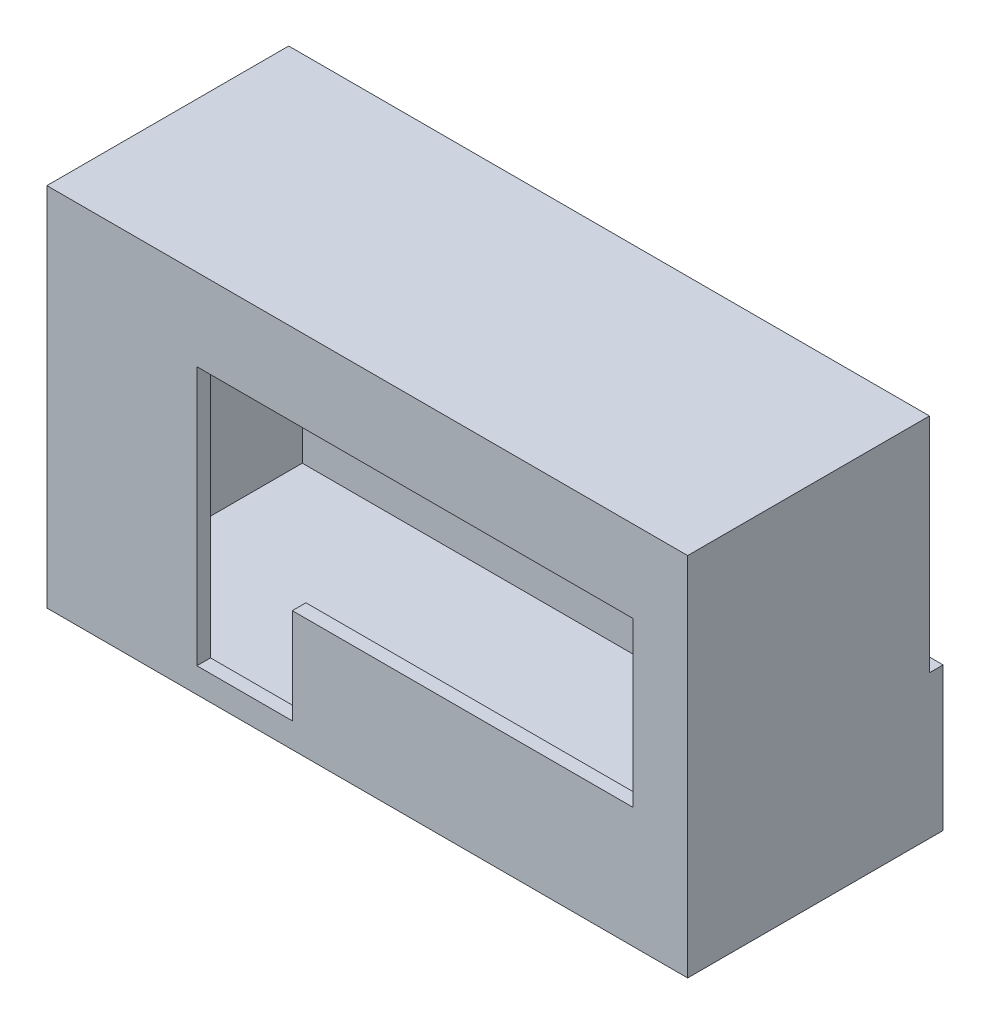
SolidWorks part; units mm, degrees
ref_plane "Спереди" through (0, 0, 0) normal (0, 0, 1) x (1, 0, 0)
ref_plane "Сверху" through (0, 0, 0) normal (0, 1, 0) x (1, 0, 0)
ref_plane "Справа" through (0, 0, 0) normal (1, 0, 0) x (0, 0, -1)
sketch "Эскиз16" plane through (0, 0, 0) normal (0, 0, 1) x (1, 0, 0)
  line L1 (0, 0) -> (-4500, 0)
  line L2 (0, 0) -> (0, 2500)
  line L3 (0, 2500) -> (-4500, 2500)
  line L4 (-4500, 0) -> (-4500, 2500)
  line L5 (-3500, 100) -> (-2800, 100)
  line L6 (-3500, 100) -> (-3500, 2000)
  line L7 (-3500, 2000) -> (-2800, 2000)
  line L8 (-2800, 100) -> (-2800, 2000)
  line L9 (-2800, 2000) -> (-300, 2000)
  line L10 (-2800, 2000) -> (-2800, 800)
  line L11 (-2800, 800) -> (-300, 800)
  line L12 (-300, 2000) -> (-300, 800)
  dimension "D1" = 2500
  dimension "D2" = 4500
  dimension "D3" = 800
  dimension "D4" = 100
  dimension "D5" = 1200
  dimension "D6" = 700
  dimension "D7" = 1000
  dimension "D8" = 300
extrude "Бобышка-Вытянуть5" add sketch "Эскиз16" along normal blind 100 contours L4 L1 L2 L3 L9 L12 L11 L8 L5 L6 L7
sketch "Эскиз19" plane through (0, 0, 0) normal (1, 0, 0) x (0, 0, -1)
  line L1 (-100, 0) -> (1673.5044, 0)
  line L2 (-100, 0) -> (-100, -83.5019)
  line L3 (-100, -83.5019) -> (1673.5044, -83.5019)
  line L4 (1673.5044, 0) -> (1673.5044, -83.5019)
  line L5 (1673.5044, 0) -> (-100, 0)
  line L6 (1673.5044, 0) -> (1673.5044, 2500)
  line L7 (1673.5044, 2500) -> (-100, 2500)
  line L8 (-100, 0) -> (-100, 2500)
extrude "Бобышка-Вытянуть6" add sketch "Эскиз19" against normal blind 4500 contours L4 L1 L2 L3
sketch "Эскиз20" plane through (0, 0, 0) normal (1, 0, 0) x (0, 0, -1)
  line L0 (1673.5044, 0) -> (1673.5044, -83.5019) construction
  line L1 (-100, 2500) -> (1673.5044, 2500)
  line L2 (-100, 2500) -> (-100, -83.5019)
  line L3 (-100, -83.5019) -> (1673.5044, -83.5019)
  line L4 (1673.5044, 2500) -> (1673.5044, -83.5019)
extrude "Бобышка-Вытянуть7" add sketch "Эскиз20" along normal blind 100
sketch "Эскиз21" plane through (-4500, 0, 0) normal (-1, 0, 0) x (0, 0, 1)
  line L1 (100, 2500) -> (-1673.5044, 2500)
  line L2 (100, 2500) -> (100, -83.5019)
  line L3 (100, -83.5019) -> (-1673.5044, -83.5019)
  line L4 (-1673.5044, 2500) -> (-1673.5044, -83.5019)
extrude "Бобышка-Вытянуть8" add sketch "Эскиз21" along normal blind 100 contours L2 L1 L4 L3
sketch "Эскиз22" plane through (0, 2500, 0) normal (0, 1, 0) x (1, 0, 0)
  line L1 (-4600, 1673.5044) -> (100, 1673.5044)
  line L2 (-4600, 1673.5044) -> (-4600, -100)
  line L3 (-4600, -100) -> (100, -100)
  line L4 (100, 1673.5044) -> (100, -100)
extrude "Бобышка-Вытянуть9" add sketch "Эскиз22" along normal blind 100
sketch "Эскиз23" plane through (0, 0, -1673.5044) normal (0, 0, -1) x (-1, 0, 0)
  line L0 (4600, 2600) -> (4600, -83.5019) construction
  line L1 (-100, -83.5019) -> (4600, -83.5019)
  line L2 (-100, -83.5019) -> (-100, 968.7802)
  line L3 (-100, 968.7802) -> (4600, 968.7802)
  line L4 (4600, -83.5019) -> (4600, 968.7802)
extrude "Бобышка-Вытянуть10" add sketch "Эскиз23" along normal blind 100
